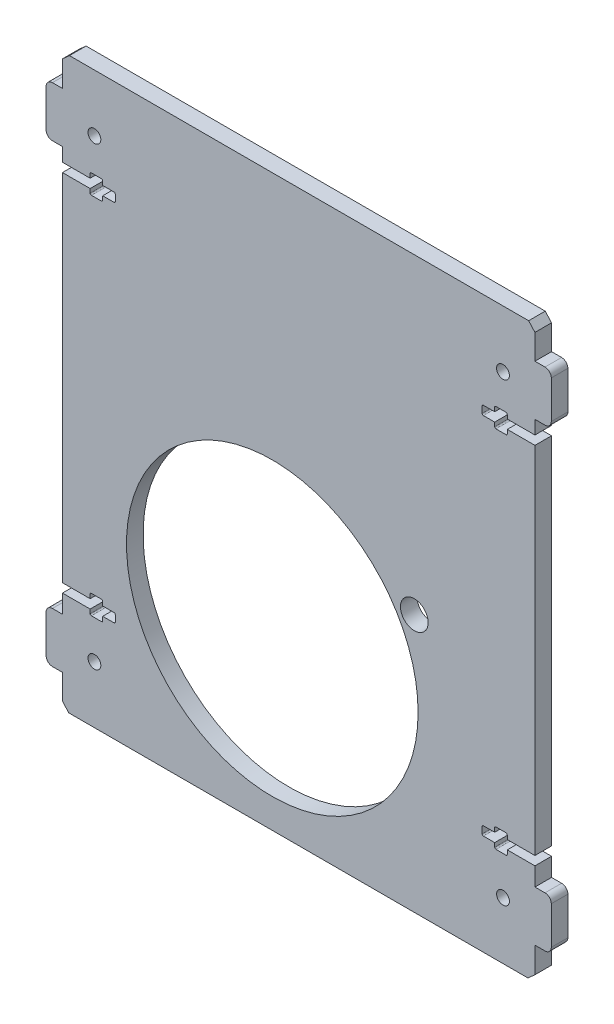
SolidWorks part; units mm, degrees
ref_plane "Front Plane" through (0, 0, 0) normal (0, 0, 1) x (1, 0, 0)
ref_plane "Top Plane" through (0, 0, 0) normal (0, 1, 0) x (1, 0, 0)
ref_plane "Right Plane" through (0, 0, 0) normal (1, 0, 0) x (0, 0, -1)
sketch "Model" plane through (0, 0, 0) normal (0, 0, 1) x (1, 0, 0)
  line L0 (93.9, 110.4235) -> (91.4, 113.2)
  line L1 (93.9, 100.5) -> (93.9, 110.4235)
  line L2 (93.9, 100.5) -> (97.9, 100.5)
  line L3 (100.4, 98) -> (100.4, 83)
  line L4 (97.9, 80.5) -> (93.9, 80.5)
  line L5 (93.9, 75.1) -> (93.9, 80.5)
  line L6 (93.9, 75.1) -> (82.9, 75.1)
  line L7 (82.9, 75.1) -> (82.9, 76.685)
  line L8 (82.4, 77.185) -> (78.4, 77.185)
  line L9 (77.9, 76.685) -> (77.9, 75.1)
  line L10 (77.9, 75.1) -> (73.4, 75.1)
  line L11 (72.9, 74.6) -> (72.9, 72.05)
  line L12 (73.4, 71.55) -> (77.9, 71.55)
  line L13 (77.9, 71.55) -> (77.9, 69.965)
  line L14 (78.4, 69.465) -> (82.4, 69.465)
  line L15 (82.9, 69.965) -> (82.9, 71.55)
  line L16 (82.9, 71.55) -> (93.9, 71.55)
  line L17 (93.9, -69.65) -> (93.9, 71.55)
  line L18 (93.9, -69.65) -> (82.9, -69.65)
  line L19 (82.9, -69.65) -> (82.9, -68.065)
  line L20 (82.4, -67.565) -> (78.4, -67.565)
  line L21 (77.9, -68.065) -> (77.9, -69.65)
  line L22 (77.9, -69.65) -> (73.4, -69.65)
  line L23 (72.9, -70.15) -> (72.9, -72.7)
  line L24 (73.4, -73.2) -> (77.9, -73.2)
  line L25 (77.9, -73.2) -> (77.9, -74.785)
  line L26 (78.4, -75.285) -> (82.4, -75.285)
  line L27 (82.9, -74.785) -> (82.9, -73.2)
  line L28 (82.9, -73.2) -> (93.9, -73.2)
  line L29 (93.9, -80.5) -> (93.9, -73.2)
  line L30 (93.9, -80.5) -> (97.9, -80.5)
  line L31 (100.4, -83) -> (100.4, -98)
  line L32 (97.9, -100.5) -> (93.9, -100.5)
  line L33 (93.9, -110.7) -> (93.9, -100.5)
  line L34 (91.1235, -113.2) -> (93.9, -110.7)
  line L35 (-91.4, -113.2) -> (91.1235, -113.2)
  line L36 (-93.9, -110.4235) -> (-91.4, -113.2)
  line L37 (-93.9, -100.5) -> (-93.9, -110.4235)
  line L38 (-97.9, -100.5) -> (-93.9, -100.5)
  line L39 (-100.4, -83) -> (-100.4, -98)
  line L40 (-93.9, -80.5) -> (-97.9, -80.5)
  line L41 (-93.9, -73.2) -> (-93.9, -80.5)
  line L42 (-82.9, -73.2) -> (-93.9, -73.2)
  line L43 (-82.9, -74.785) -> (-82.9, -73.2)
  line L44 (-78.4, -75.285) -> (-82.4, -75.285)
  line L45 (-77.9, -73.2) -> (-77.9, -74.785)
  line L46 (-73.4, -73.2) -> (-77.9, -73.2)
  line L47 (-72.9, -70.15) -> (-72.9, -72.7)
  line L48 (-77.9, -69.65) -> (-73.4, -69.65)
  line L49 (-77.9, -68.065) -> (-77.9, -69.65)
  line L50 (-82.4, -67.565) -> (-78.4, -67.565)
  line L51 (-82.9, -69.65) -> (-82.9, -68.065)
  line L52 (-93.9, -69.65) -> (-82.9, -69.65)
  line L53 (-93.9, 71.55) -> (-93.9, -69.65)
  line L54 (-82.9, 71.55) -> (-93.9, 71.55)
  line L55 (-82.9, 69.965) -> (-82.9, 71.55)
  line L56 (-78.4, 69.465) -> (-82.4, 69.465)
  line L57 (-77.9, 71.55) -> (-77.9, 69.965)
  line L58 (-73.4, 71.55) -> (-77.9, 71.55)
  line L59 (-72.9, 74.6) -> (-72.9, 72.05)
  line L60 (-77.9, 75.1) -> (-73.4, 75.1)
  line L61 (-77.9, 76.685) -> (-77.9, 75.1)
  line L62 (-82.4, 77.185) -> (-78.4, 77.185)
  line L63 (-82.9, 75.1) -> (-82.9, 76.685)
  line L64 (-93.9, 75.1) -> (-82.9, 75.1)
  line L65 (-93.9, 80.5) -> (-93.9, 75.1)
  line L66 (-97.9, 80.5) -> (-93.9, 80.5)
  line L67 (-100.4, 98) -> (-100.4, 83)
  line L68 (-93.9, 100.5) -> (-97.9, 100.5)
  line L69 (-93.9, 110.7) -> (-93.9, 100.5)
  line L70 (-91.1235, 113.2) -> (-93.9, 110.7)
  line L71 (91.4, 113.2) -> (-91.1235, 113.2)
  circle A0 centre (-10.4932, -43.592) radius 57.9542
  circle A1 centre (81.2, -90.5) radius 2.55
  circle A2 centre (81.2, 90.5) radius 2.55
  circle A3 centre (-81.2, 90.5) radius 2.55
  circle A4 centre (-81.2, -90.5) radius 2.55
  circle A5 centre (45.952, -10.7248) radius 5.5
  arc A6 (100.4, 98) -> (97.9, 100.5) centre (97.9, 98) ccw
  arc A7 (97.9, 80.5) -> (100.4, 83) centre (97.9, 83) ccw
  arc A8 (82.9, 76.685) -> (82.4, 77.185) centre (82.4, 76.685) ccw
  arc A9 (78.4, 77.185) -> (77.9, 76.685) centre (78.4, 76.685) ccw
  arc A10 (73.4, 75.1) -> (72.9, 74.6) centre (73.4, 74.6) ccw
  arc A11 (72.9, 72.05) -> (73.4, 71.55) centre (73.4, 72.05) ccw
  arc A12 (77.9, 69.965) -> (78.4, 69.465) centre (78.4, 69.965) ccw
  arc A13 (82.4, 69.465) -> (82.9, 69.965) centre (82.4, 69.965) ccw
  arc A14 (82.9, -68.065) -> (82.4, -67.565) centre (82.4, -68.065) ccw
  arc A15 (78.4, -67.565) -> (77.9, -68.065) centre (78.4, -68.065) ccw
  arc A16 (73.4, -69.65) -> (72.9, -70.15) centre (73.4, -70.15) ccw
  arc A17 (72.9, -72.7) -> (73.4, -73.2) centre (73.4, -72.7) ccw
  arc A18 (77.9, -74.785) -> (78.4, -75.285) centre (78.4, -74.785) ccw
  arc A19 (82.4, -75.285) -> (82.9, -74.785) centre (82.4, -74.785) ccw
  arc A20 (100.4, -83) -> (97.9, -80.5) centre (97.9, -83) ccw
  arc A21 (97.9, -100.5) -> (100.4, -98) centre (97.9, -98) ccw
  arc A22 (-100.4, -98) -> (-97.9, -100.5) centre (-97.9, -98) ccw
  arc A23 (-97.9, -80.5) -> (-100.4, -83) centre (-97.9, -83) ccw
  arc A24 (-82.9, -74.785) -> (-82.4, -75.285) centre (-82.4, -74.785) ccw
  arc A25 (-78.4, -75.285) -> (-77.9, -74.785) centre (-78.4, -74.785) ccw
  arc A26 (-73.4, -73.2) -> (-72.9, -72.7) centre (-73.4, -72.7) ccw
  arc A27 (-72.9, -70.15) -> (-73.4, -69.65) centre (-73.4, -70.15) ccw
  arc A28 (-77.9, -68.065) -> (-78.4, -67.565) centre (-78.4, -68.065) ccw
  arc A29 (-82.4, -67.565) -> (-82.9, -68.065) centre (-82.4, -68.065) ccw
  arc A30 (-82.9, 69.965) -> (-82.4, 69.465) centre (-82.4, 69.965) ccw
  arc A31 (-78.4, 69.465) -> (-77.9, 69.965) centre (-78.4, 69.965) ccw
  arc A32 (-73.4, 71.55) -> (-72.9, 72.05) centre (-73.4, 72.05) ccw
  arc A33 (-72.9, 74.6) -> (-73.4, 75.1) centre (-73.4, 74.6) ccw
  arc A34 (-77.9, 76.685) -> (-78.4, 77.185) centre (-78.4, 76.685) ccw
  arc A35 (-82.4, 77.185) -> (-82.9, 76.685) centre (-82.4, 76.685) ccw
  arc A36 (-100.4, 83) -> (-97.9, 80.5) centre (-97.9, 83) ccw
  arc A37 (-97.9, 100.5) -> (-100.4, 98) centre (-97.9, 98) ccw
extrude "Boss-Extrude1" add sketch "Model" along normal blind 6.6
